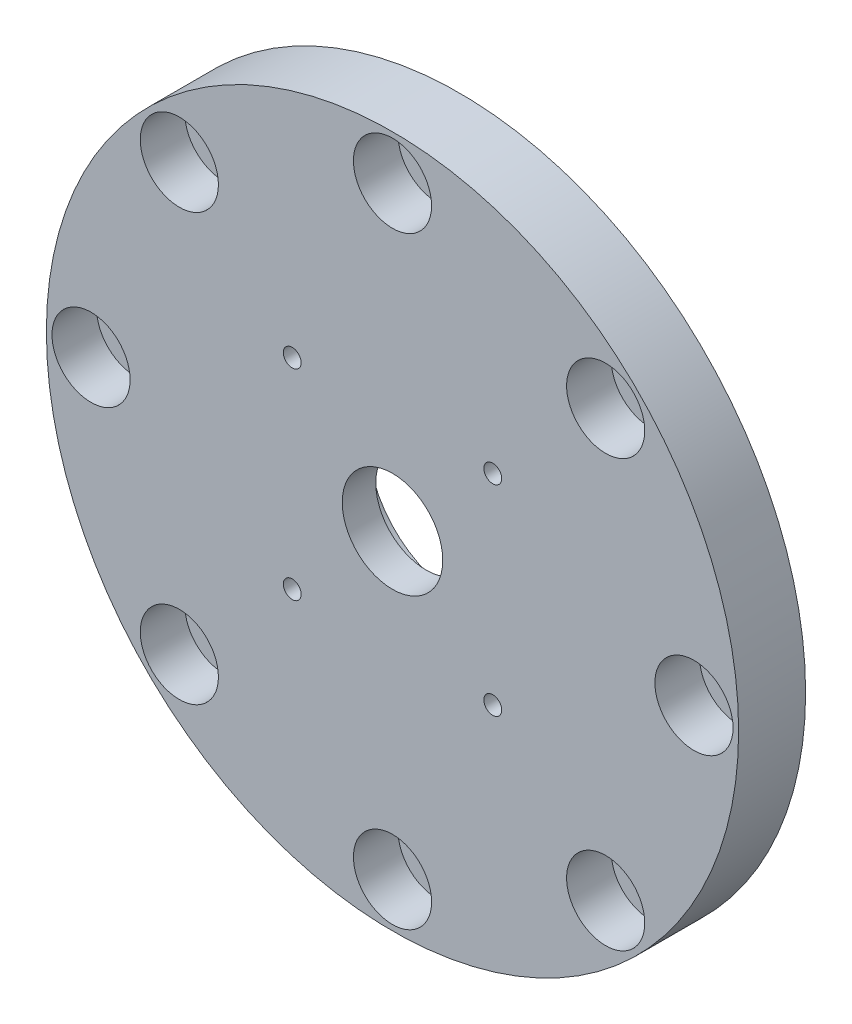
SolidWorks part; units mm, degrees
ref_plane "Front Plane" through (0, 0, 0) normal (0, 0, 1) x (1, 0, 0)
ref_plane "Top Plane" through (0, 0, 0) normal (0, 1, 0) x (1, 0, 0)
ref_plane "Right Plane" through (0, 0, 0) normal (1, 0, 0) x (0, 0, -1)
sketch "Sketch1" plane through (0, 0, 0) normal (0, 0, 1) x (1, 0, 0)
  line L11 (0, 0) -> (8.9803, 8.9803) construction
  line L17 (0, 0) -> (-27, 0) construction
  circle A2 centre (0, 0) radius 4.5
  circle A3 centre (0, 0) radius 12.7 construction
  circle A11 centre (8.9803, 8.9803) radius 0.8
  circle A12 centre (8.9803, -8.9803) radius 0.8
  circle A13 centre (-8.9803, -8.9803) radius 0.8
  circle A14 centre (-8.9803, 8.9803) radius 0.8
  circle A33 centre (0, 0) radius 24 construction
  circle A34 centre (0, 0) radius 31
  circle A35 centre (-27, 0) radius 1.55
  circle A36 centre (-19.0919, 19.0919) radius 1.55
  circle A37 centre (0, 27) radius 1.55
  circle A38 centre (19.0919, 19.0919) radius 1.55
  circle A39 centre (27, 0) radius 1.55
  circle A40 centre (19.0919, -19.0919) radius 1.55
  circle A41 centre (0, -27) radius 1.55
  circle A42 centre (-19.0919, -19.0919) radius 1.55
  point P7 (0, 0)
  point P10 (0, 0)
  point P12 (0, 0)
  point P16 (0, 0)
  point P17 (0, 0)
  point P20 (0, 0)
  point P30 (0, 0)
  point P39 (0, 0)
  point P47 (0, 0)
  point P64 (0, 0)
  dimension "D1" = 4
extrude "Boss-Extrude2" add sketch "Sketch1" along normal blind 6
sketch "Sketch5" plane through (0, 0, 0) normal (0, 0, -1) x (-1, 0, 0)
  circle A0 centre (0, 0) radius 8.2
extrude "Cut-Extrude3" cut sketch "Sketch5" against normal blind 3
sketch "Sketch6" plane through (0, 0, 6) normal (0, 0, 1) x (1, 0, 0)
  circle A7 centre (0, 27) radius 3.5
  circle A8 centre (19.0919, 19.0919) radius 3.5
  circle A9 centre (27, 0) radius 3.5
  circle A10 centre (19.0919, -19.0919) radius 3.5
  circle A11 centre (0, -27) radius 3.5
  circle A12 centre (-19.0919, -19.0919) radius 3.5
  circle A13 centre (-27, 0) radius 3.5
  circle A14 centre (-19.0919, 19.0919) radius 3.5
  point P11 (-3.75, 3.75)
  point P29 (0, 0)
  point P31 (0, 0)
  dimension "D2" = 8
extrude "Cut-Extrude4" cut sketch "Sketch6" against normal blind 4
